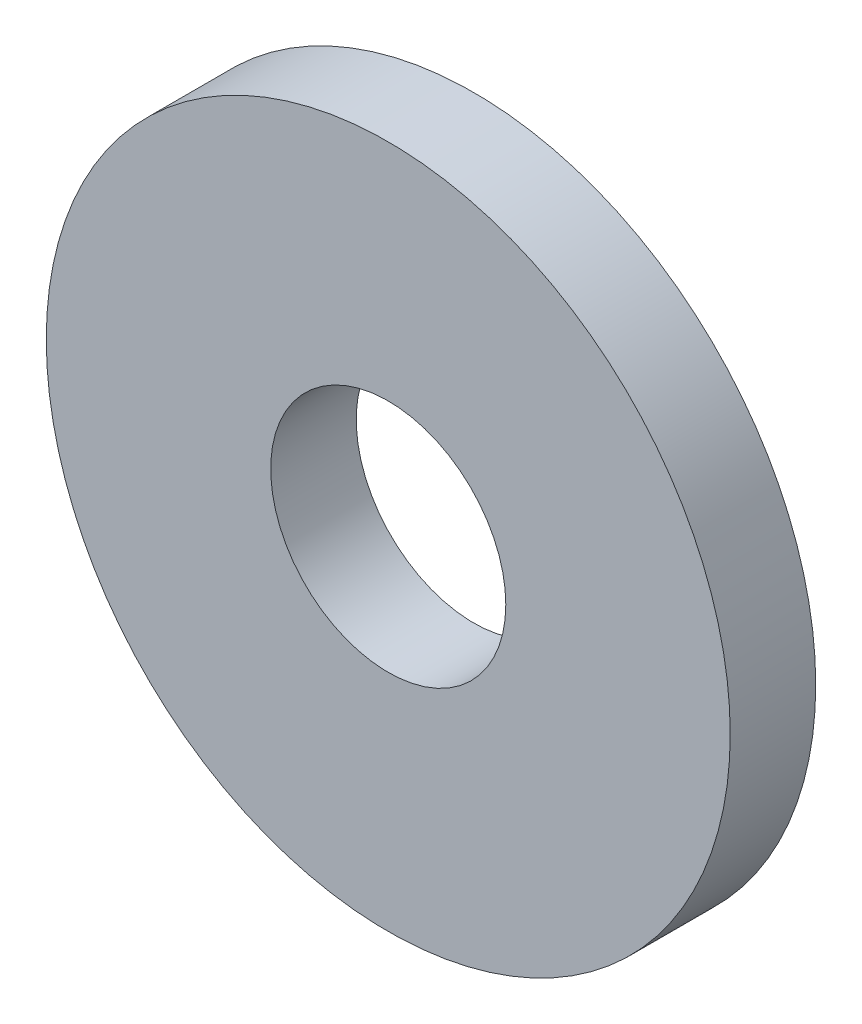
SolidWorks part; units mm, degrees
material "AISI 304"
ref_plane "Front Plane" through (0, 0, 0) normal (0, 0, 1) x (1, 0, 0)
ref_plane "Top Plane" through (0, 0, 0) normal (0, 1, 0) x (1, 0, 0)
ref_plane "Right Plane" through (0, 0, 0) normal (1, 0, 0) x (0, 0, -1)
sketch "Sketch1" plane through (0, 0, 0) normal (0, 0, 1) x (1, 0, 0)
  circle A0 centre (0, 0) radius 1.6
  circle A1 centre (0, 0) radius 0.55
  dimension "OD" = 3.2
  dimension "ID1" = 1.1
extrude "Boss-Extrude1" add sketch "Sketch1" along normal blind 0.4
